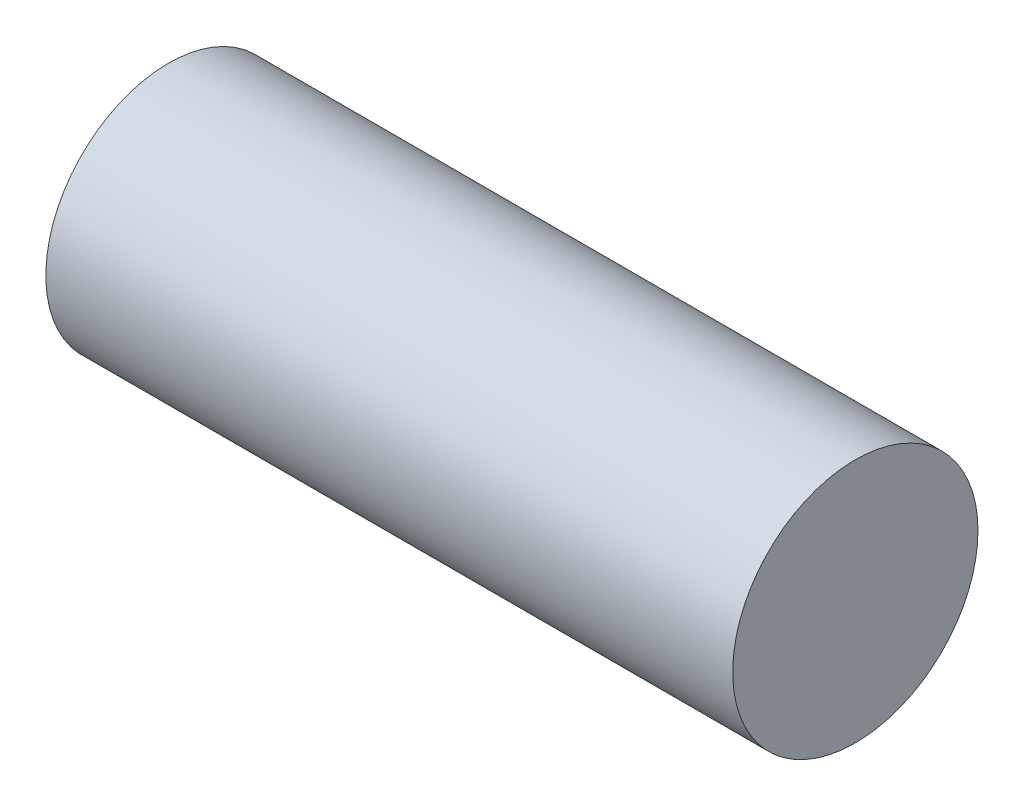
SolidWorks part; units mm, degrees
ref_plane "Front Plane" through (0, 0, 0) normal (0, 0, 1) x (1, 0, 0)
ref_plane "Top Plane" through (0, 0, 0) normal (0, 1, 0) x (1, 0, 0)
ref_plane "Right Plane" through (0, 0, 0) normal (1, 0, 0) x (0, 0, -1)
sketch "Sketch1" plane through (0, 0, 0) normal (1, 0, 0) x (0, 0, -1)
  circle A0 centre (0, 0) radius 3.175
  dimension "D1" = 6.35
extrude "Boss-Extrude1" add sketch "Sketch1" along normal mid plane 17.78
